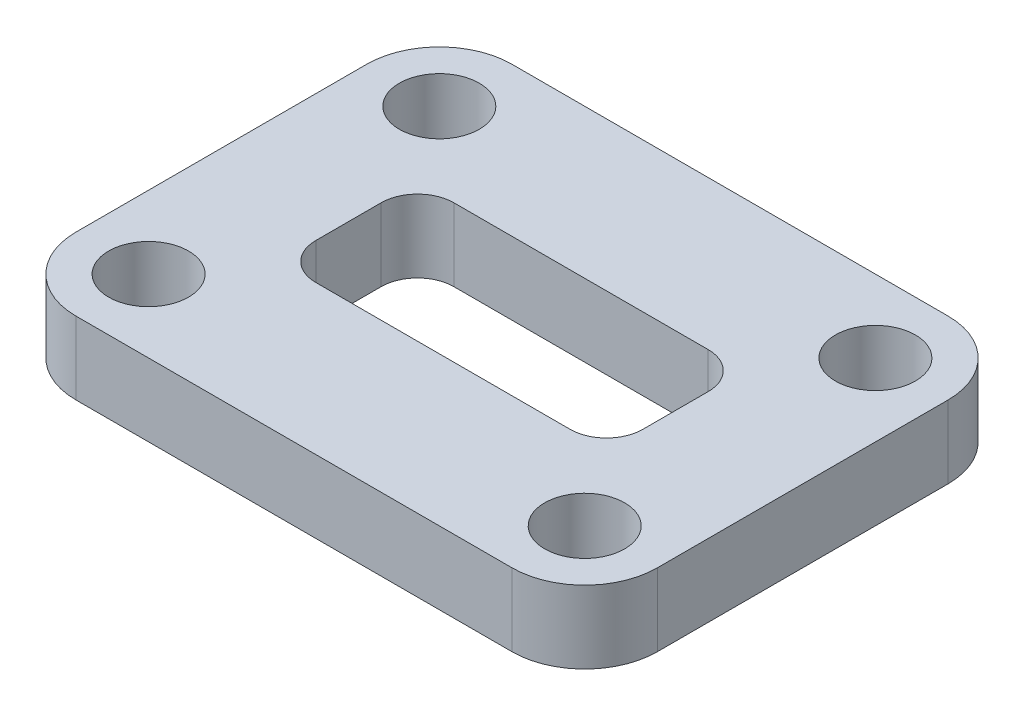
SolidWorks part; units mm, degrees
material "Thornel Mat VMA"
ref_plane "前视基准面" through (0, 0, 0) normal (0, 0, 1) x (1, 0, 0)
ref_plane "上视基准面" through (0, 0, 0) normal (0, 1, 0) x (1, 0, 0)
ref_plane "右视基准面" through (0, 0, 0) normal (1, 0, 0) x (0, 0, -1)
sketch "草图1" plane through (0, 0, 0) normal (0, 1, 0) x (1, 0, 0)
  line L1 (-8, -6) -> (8, -6)
  line L2 (-8, -6) -> (-8, 6)
  line L3 (-8, 6) -> (8, 6)
  line L4 (8, -6) -> (8, 6)
  line L5 (0, 6) -> (0, -6) construction
  line L6 (-8, 0) -> (8, 0) construction
  line L11 (-4.5, -1.9) -> (4.5, -1.9)
  line L12 (-4.5, -1.9) -> (-4.5, 1.9)
  line L13 (-4.5, 1.9) -> (4.5, 1.9)
  line L14 (4.5, -1.9) -> (4.5, 1.9)
  line L15 (0, 1.9) -> (0, -1.9) construction
  line L16 (-4.5, 0) -> (4.5, 0) construction
  circle A0 centre (-6, 4) radius 1.1
  circle A1 centre (-6, -4) radius 1.1
  circle A2 centre (6, -4) radius 1.1
  circle A3 centre (6, 4) radius 1.1
  point P0 (0, 0)
  point P12 (0, 0)
  dimension "D5" = 2.2
  dimension "D1" = 16
  dimension "D2" = 12
  dimension "D3" = 12
  dimension "D4" = 8
  dimension "D6" = 3.8
  dimension "D7" = 9
extrude "凸台-拉伸1" add sketch "草图1" along normal blind 2
fillet "圆角1" radius 2 4 edges at (-8, 1, 6) (8, 1, -6) (8, 1, 6) (-8, 1, -6)
fillet "圆角2" radius 1 4 edges at (-4.5, 1, -1.9) (-4.5, 1, 1.9) (4.5, 1, 1.9) (4.5, 1, -1.9)
